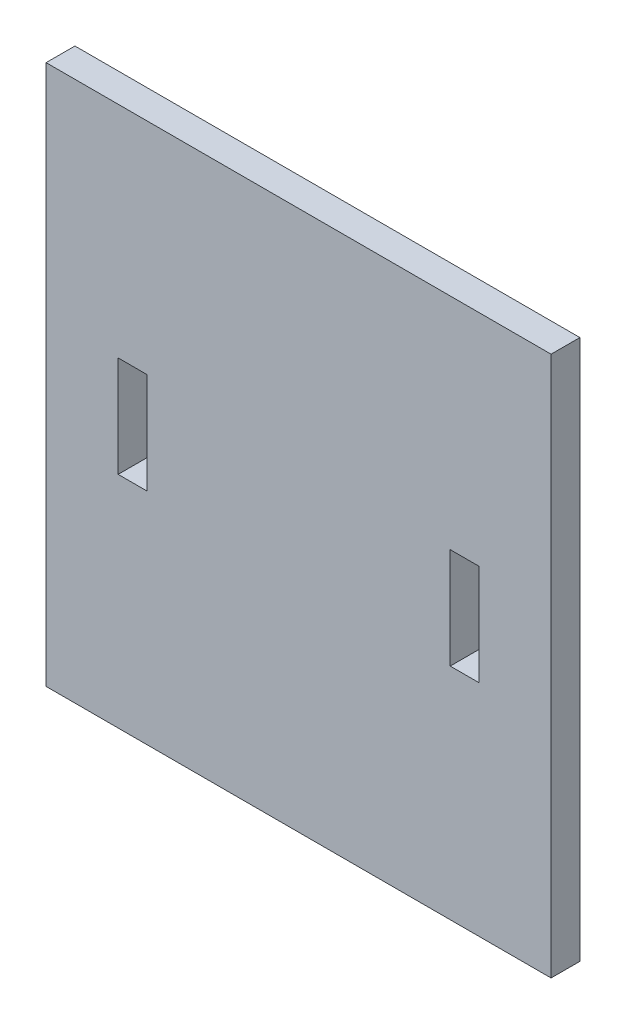
SolidWorks part; units mm, degrees
ref_plane "Alzado" through (0, 0, 0) normal (0, 0, 1) x (1, 0, 0)
ref_plane "Planta" through (0, 0, 0) normal (0, 1, 0) x (1, 0, 0)
ref_plane "Vista lateral" through (0, 0, 0) normal (1, 0, 0) x (0, 0, -1)
sketch "Croquis1" plane through (0, 0, 0) normal (0, 0, 1) x (1, 0, 0)
  line L0 (0, -37.5) -> (0, 0) construction
  line L1 (35.05, 37.5) -> (-35.05, 37.5)
  line L2 (35.05, 37.5) -> (35.05, -37.5)
  line L3 (35.05, -37.5) -> (-35.05, -37.5)
  line L4 (-35.05, 37.5) -> (-35.05, -37.5)
  line L5 (35.05, 37.5) -> (-35.05, -37.5) construction
  line L6 (35.05, -37.5) -> (-35.05, 37.5) construction
  line L7 (-35.05, 0) -> (-25.05, 0) construction
  line L8 (-25.05, 0) -> (-25.05, 7) construction
  line L9 (-25.05, 0) -> (-25.05, -7) construction
  line L10 (-25.05, 7) -> (-25.05, -7)
  line L11 (-25.05, -7) -> (-21.05, -7)
  line L12 (-21.05, -7) -> (-21.05, 7)
  line L13 (-21.05, 7) -> (-25.05, 7)
  line L14 (21.05, 7) -> (25.05, 7)
  line L15 (25.05, -7) -> (21.05, -7)
  line L16 (25.05, 7) -> (25.05, -7)
  line L17 (21.05, -7) -> (21.05, 7)
  point P0 (0, 0)
  dimension "D1" = 70.1
  dimension "D2" = 75
  dimension "D3" = 50.1
  dimension "D4" = 42.1
extrude "Saliente-Extruir1" add sketch "Croquis1" along normal blind 4
